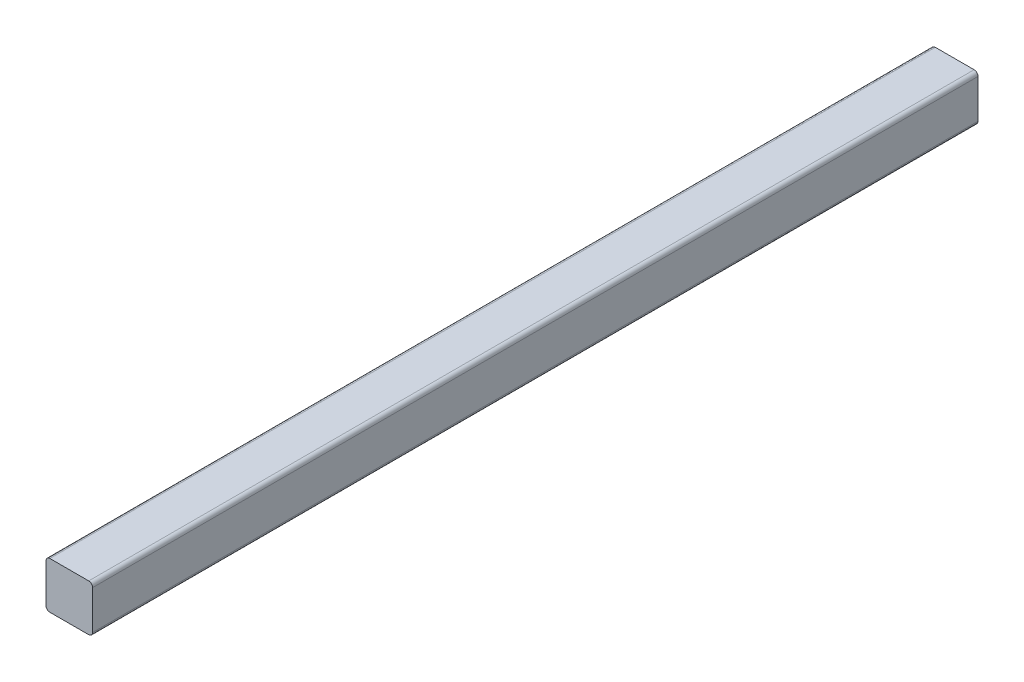
SolidWorks part; units mm, degrees
ref_plane "Front Plane" through (0, 0, 0) normal (0, 0, 1) x (1, 0, 0)
ref_plane "Top Plane" through (0, 0, 0) normal (0, 1, 0) x (1, 0, 0)
ref_plane "Right Plane" through (0, 0, 0) normal (1, 0, 0) x (0, 0, -1)
sketch "Sketch1" plane through (0, 0, 0) normal (0, 0, 1) x (1, 0, 0)
  line L1 (-19.05, -19.05) -> (19.05, -19.05)
  line L2 (-19.05, -19.05) -> (-19.05, 19.05)
  line L3 (-19.05, 19.05) -> (19.05, 19.05)
  line L4 (19.05, -19.05) -> (19.05, 19.05)
  line L5 (-19.05, -19.05) -> (19.05, 19.05) construction
  line L6 (-19.05, 19.05) -> (19.05, -19.05) construction
  point P0 (0, 0)
  dimension "D1" = 38.1
  dimension "D2" = 38.1
extrude "Boss-Extrude1" add sketch "Sketch1" along normal blind 723.9
fillet "Fillet1" radius 3.175 4 edges at (-19.05, 19.05, 361.95) (-19.05, -19.05, 361.95) (19.05, -19.05, 361.95) (19.05, 19.05, 361.95)
